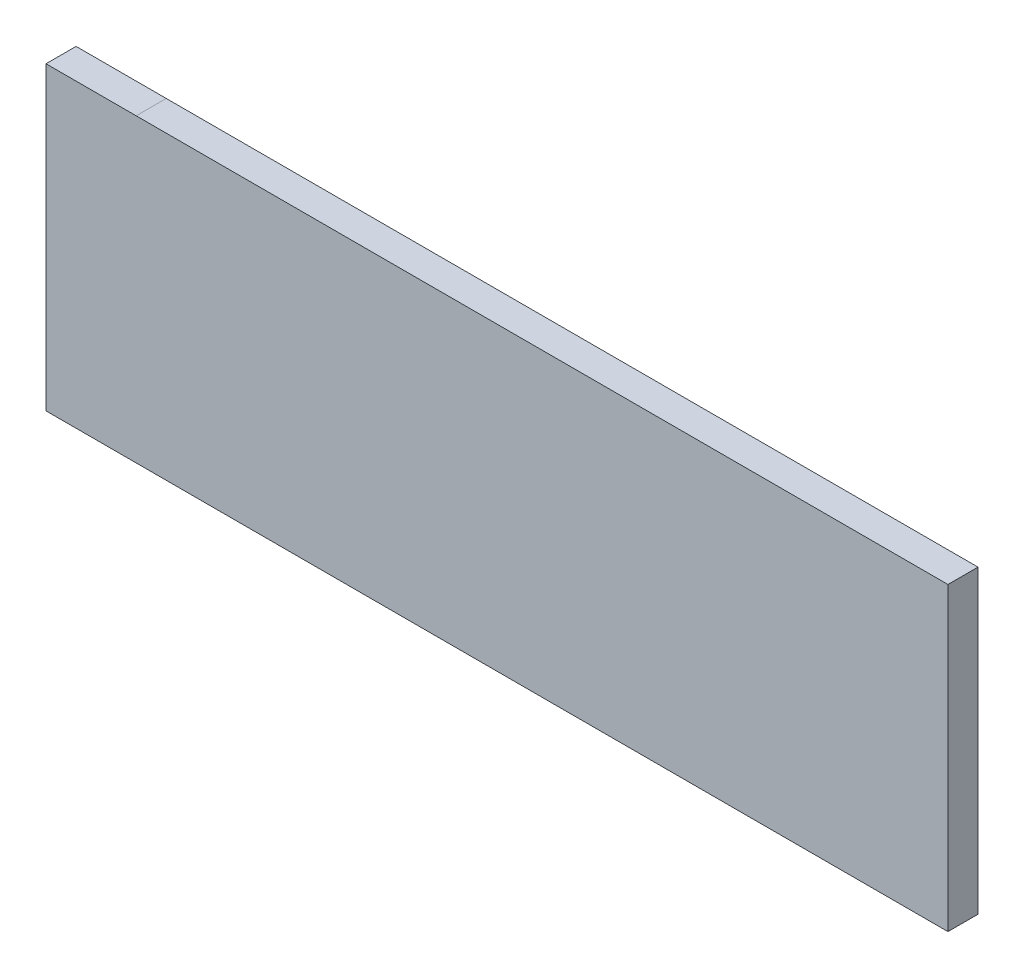
SolidWorks part; units mm, degrees
ref_plane "Front Plane" through (0, 0, 0) normal (0, 0, 1) x (1, 0, 0)
ref_plane "Top Plane" through (0, 0, 0) normal (0, 1, 0) x (1, 0, 0)
ref_plane "Right Plane" through (0, 0, 0) normal (1, 0, 0) x (0, 0, -1)
sketch "Sketch1" plane through (0, 0, 0) normal (0, 0, 1) x (1, 0, 0)
  line L1 (0, 0) -> (3000, 0)
  line L2 (0, 0) -> (0, 1000)
  line L3 (0, 1000) -> (3000, 1000)
  line L4 (3000, 0) -> (3000, 1000)
  dimension "D1" = 3000
  dimension "D2" = 1000
extrude "Boss-Extrude1" add sketch "Sketch1" along normal blind 100
sketch "Sketch3" plane through (0, 1000, 0) normal (0, 1, 0) x (1, 0, 0)
  line L0 (300, 0) -> (300, -100)
  line L1 (3000, 0) -> (0, 0) construction
  line L2 (3000, -100) -> (0, -100) construction
  line L3 (0, -100) -> (0, 0) construction
  dimension "D1" = 300
split line "Split Line1"
sketch "Sketch4" plane through (0, 0, 0) normal (0, -1, 0) x (1, 0, 0)
  line L0 (2700, 100) -> (2700, 0)
  line L1 (0, 100) -> (3000, 100) construction
  line L2 (3000, 100) -> (3000, 0) construction
  line L3 (0, 0) -> (3000, 0) construction
  point P6 (2700, 0)
  dimension "D1" = 300
split line "Split Line2"
